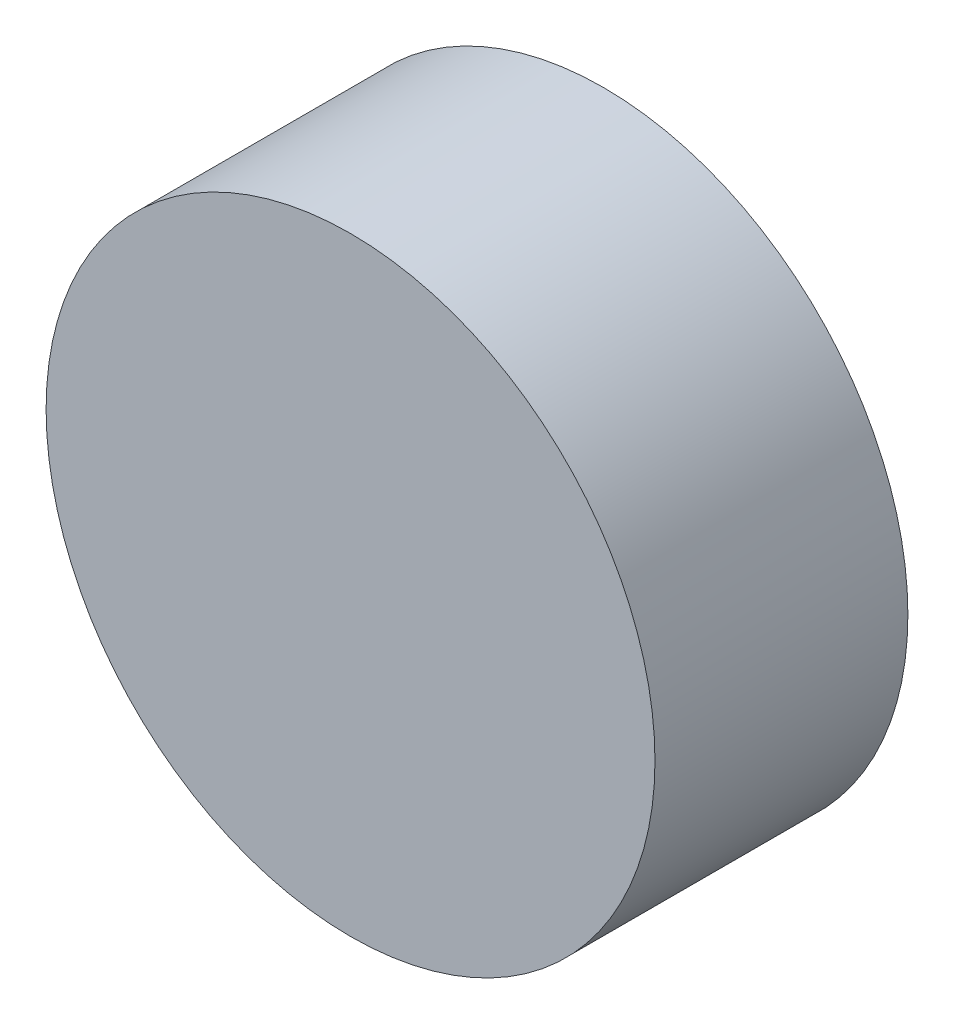
SolidWorks part; units mm, degrees
ref_plane "前视基准面" through (0, 0, 0) normal (0, 0, 1) x (1, 0, 0)
ref_plane "上视基准面" through (0, 0, 0) normal (0, 1, 0) x (1, 0, 0)
ref_plane "右视基准面" through (0, 0, 0) normal (1, 0, 0) x (0, 0, -1)
other "Configuration Table"
sketch "草图1" plane through (0, 0, 0) normal (0, 0, 1) x (1, 0, 0)
  circle A0 centre (0, 0) radius 32.5
  dimension "D1" = 65
extrude "凸台-拉伸1" add sketch "草图1" along normal blind 27
sketch "草图2" plane through (0, 0, 0) normal (0, 0, -1) x (-1, 0, 0)
  circle A0 centre (0, 0) radius 20
  dimension "D1" = 40
extrude "切除-拉伸1" cut sketch "草图2" against normal blind 10
sketch "草图3" plane through (0, 0, 10) normal (0, 0, -1) x (-1, 0, 0)
  line L0 (0, -6.9282) -> (0, 0) construction
  line L1 (6, 3.4641) -> (0, 6.9282)
  line L2 (0, 6.9282) -> (-6, 3.4641)
  line L3 (-6, 3.4641) -> (-6, -3.4641)
  line L4 (-6, -3.4641) -> (0, -6.9282)
  line L5 (0, -6.9282) -> (6, -3.4641)
  line L6 (6, -3.4641) -> (6, 3.4641)
  circle A0 centre (0, 0) radius 6 construction
  dimension "D1" = 12
extrude "切除-拉伸2" cut sketch "草图3" against normal blind 6
